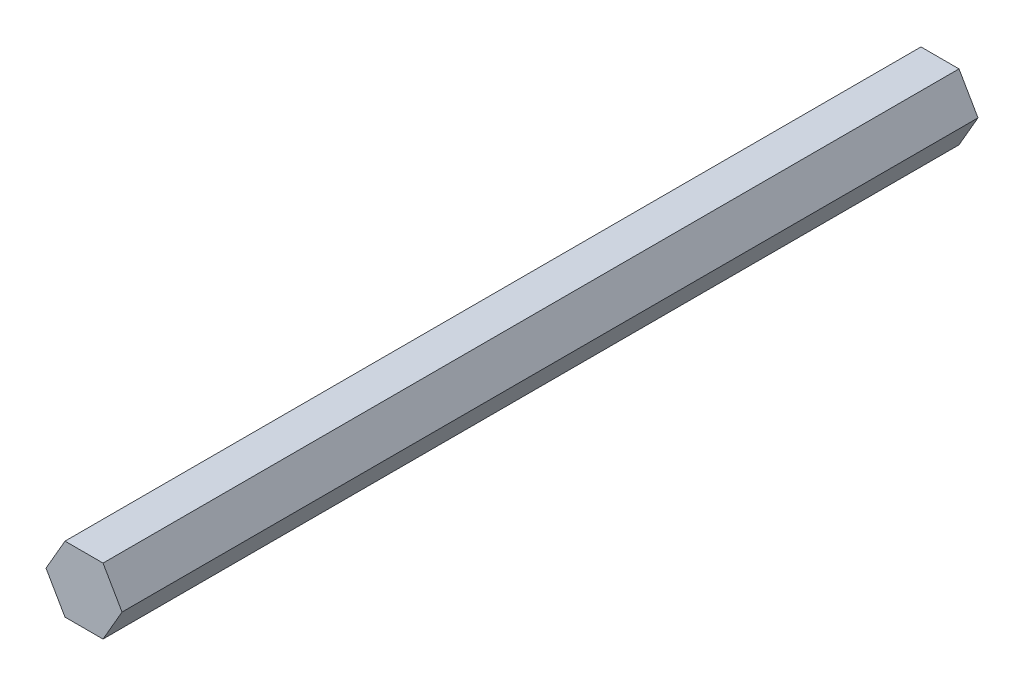
SolidWorks part; units mm, degrees
ref_plane "Front Plane" through (0, 0, 0) normal (0, 0, 1) x (1, 0, 0)
ref_plane "Top Plane" through (0, 0, 0) normal (0, 1, 0) x (1, 0, 0)
ref_plane "Right Plane" through (0, 0, 0) normal (1, 0, 0) x (0, 0, -1)
sketch "Sketch1" plane through (0, 0, 0) normal (0, 0, 1) x (1, 0, 0)
  line L1 (3.6635, -6.3515) -> (7.3323, -0.003)
  line L2 (7.3323, -0.003) -> (3.6688, 6.3485)
  line L3 (3.6688, 6.3485) -> (-3.6635, 6.3515)
  line L4 (-3.6635, 6.3515) -> (-7.3323, 0.003)
  line L5 (-7.3323, 0.003) -> (-3.6688, -6.3485)
  line L6 (-3.6688, -6.3485) -> (3.6635, -6.3515)
  circle A0 centre (0, 0) radius 6.35 construction
  dimension "D1" = 12.7
extrude "Boss-Extrude1" add sketch "Sketch1" along normal blind 165.1
sketch "Sketch2" plane through (0, 0, 0) normal (0, 0, -1) x (-1, 0, 0)
  circle A0 centre (0, 0) radius 6.35
